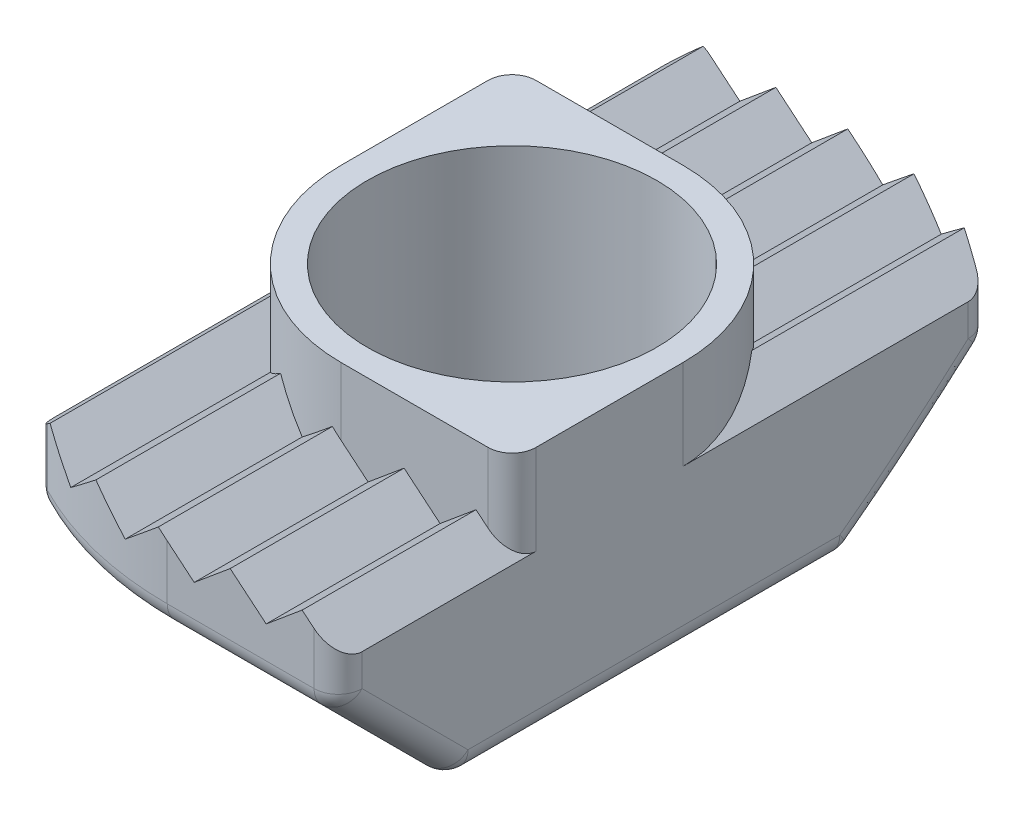
SolidWorks part; units mm, degrees
material "Plain Carbon Steel"
ref_plane "Front Plane" through (0, 0, 0) normal (0, 0, 1) x (1, 0, 0)
ref_plane "Top Plane" through (0, 0, 0) normal (0, 1, 0) x (1, 0, 0)
ref_plane "Right Plane" through (0, 0, 0) normal (1, 0, 0) x (0, 0, -1)
sketch "Sketch1" plane through (0, 0, 0) normal (0, 1, 0) x (1, 0, 0)
  line L1 (-2.85, -5.75) -> (2.85, -5.75)
  line L2 (-2.85, -5.75) -> (-2.85, 5.75)
  line L3 (-2.85, 5.75) -> (2.85, 5.75)
  line L4 (2.85, -5.75) -> (2.85, 5.75)
  line L5 (-2.85, -5.75) -> (2.85, 5.75) construction
  line L6 (-2.85, 5.75) -> (2.85, -5.75) construction
  point P0 (0, 0)
  dimension "D1" = 5.7
  dimension "D2" = 11.5
extrude "Boss-Extrude1" add sketch "Sketch1" along normal mid plane 2.7
sketch "Sketch2" plane through (0, 0, 5.75) normal (0, 0, 1) x (1, 0, 0)
  line L0 (2.25, 1.85) -> (2.85, 1.35)
  line L1 (2.25, 1.85) -> (1.65, 1.35)
  line L2 (-2.85, 1.35) -> (2.85, 1.35) construction
  line L3 (2.85, 1.35) -> (1.65, 1.35)
  line L4 (1.05, 1.85) -> (0.45, 1.35)
  line L5 (1.05, 1.85) -> (1.65, 1.35)
  line L6 (1.65, 1.35) -> (0.45, 1.35)
  line L7 (-0.15, 1.85) -> (-0.75, 1.35)
  line L8 (-0.15, 1.85) -> (0.45, 1.35)
  line L9 (0.45, 1.35) -> (-0.75, 1.35)
  line L10 (-1.35, 1.85) -> (-1.95, 1.35)
  line L11 (-1.35, 1.85) -> (-0.75, 1.35)
  line L12 (-0.75, 1.35) -> (-1.95, 1.35)
  line L13 (-2.55, 1.85) -> (-2.85, 1.6)
  line L14 (-2.55, 1.85) -> (-1.95, 1.35)
  line L15 (-1.95, 1.35) -> (-2.85, 1.35)
  line L16 (-2.85, 1.35) -> (-2.85, 1.6)
  dimension "D1" = 1.2
  dimension "D2" = 0.5
  dimension "D3" = 5
extrude "Boss-Extrude2" add sketch "Sketch2" against normal up to surface (11.5 mm away) up to face at (0, 0, -5.75)
ref_plane "Plane2" through (0, 1.35, 0) normal (0, -1, 0) x (1, 0, 0)
sketch "Sketch7" plane through (0, 1.35, 0) normal (0, -1, 0) x (1, 0, 0)
  line L1 (0, 2.85) -> (2.45, 2.85)
  line L2 (-2.85, 0) -> (-2.85, -2.45)
  line L3 (-2.45, -2.85) -> (0, -2.85)
  line L4 (2.85, 2.45) -> (2.85, 0)
  line L5 (-2.0153, 2.0153) -> (2.0153, -2.0153) construction
  line L6 (-2.85, -2.85) -> (2.85, 2.85) construction
  arc A0 (0, 2.85) -> (-2.85, 0) centre (0, 0) ccw
  arc A1 (0, -2.85) -> (2.85, 0) centre (0, 0) ccw
  arc A2 (-2.85, -2.45) -> (-2.45, -2.85) centre (-2.45, -2.45) ccw
  arc A3 (2.45, 2.85) -> (2.85, 2.45) centre (2.45, 2.45) cw
  point P0 (0, 0)
  dimension "D1" = 0.4
extrude "Boss-Extrude4" add sketch "Sketch7" against normal blind 1.5
sketch "Sketch8" plane through (0, -1.35, 0) normal (0, -1, 0) x (1, 0, 0)
  line L0 (-2.85, 4.994) -> (-2.85, 5.75)
  line L1 (0, -5.75) -> (2.85, -5.75)
  line L3 (-2.85, 5.75) -> (0, 5.75)
  line L4 (2.85, -5.75) -> (2.85, -4.994)
  arc A1 (0, 5.75) -> (-2.85, 4.994) centre (0, 0) ccw
  arc A2 (0, -5.75) -> (2.85, -4.994) centre (0, 0) ccw
  point P0 (0, 0)
extrude "Cut-Extrude3" cut sketch "Sketch8" against normal blind 3.5
chamfer "Chamfer2" distance 2 angle 45 4 edges at (1.4743, -1.35, -5.5578) (-1.425, -1.35, -5.75) (-1.4743, -1.35, 5.5578) (1.425, -1.35, 5.75)
hole_wizard "#10-32 Tapped Hole3" positions "Sketch10" profile "Sketch9" tap size "#10-32" standard "Ansi Inch"
sketch "Sketch10" plane through (0, -1.35, 0) normal (0, -1, 0) x (1, 0, 0)
  point P1 (0, 0)
sketch "Sketch9" plane through (0, -1.35, 0) normal (1, 0, 0) x (0, 0, -1)
  line L0 (0, 0) -> (0, 13.2428)
  line L1 (0, 13.2428) -> (2.0193, 12.0294)
  line L2 (2.0193, 12.0294) -> (2.0193, 9.652)
  line L3 (2.0193, 9.652) -> (2.413, 9.652)
  line L4 (2.413, 9.652) -> (2.413, 0)
  line L5 (2.413, 0) -> (0, 0)
  line L10 (0, 13.2428) -> (-2.0193, 12.0294) construction
  line L11 (0, -6.35) -> (0, 107.95) construction
  dimension "Tap Drill Dia." = 4.0386
  dimension "Tap Drill Depth" = 12.0294
  dimension "Thread Major Dia." = 4.826
  dimension "Thread Depth" = 9.652
  dimension "Drill Angle" = 118
fillet "Fillet2" radius 0.4 17 edges at (1.425, 0.65, 5.75) (1.425, -1.35, 3.75) (-1.425, 0.65, -5.75) (-1.425, -1.35, -3.75) (-1.4743, 0.65, 5.5578) (-1.5689, -1.35, 3.406) (1.4743, 0.65, -5.5578) (1.5689, -1.35, -3.406) (2.85, 1, 5.75) (2.85, -0.35, 4.75) (-2.85, 1.125, 4.994) (-2.85, -1.35, -0.6564) (-2.85, 1.125, -5.75) (2.85, -1.35, 0.6564) (2.85, 1, -4.994)
